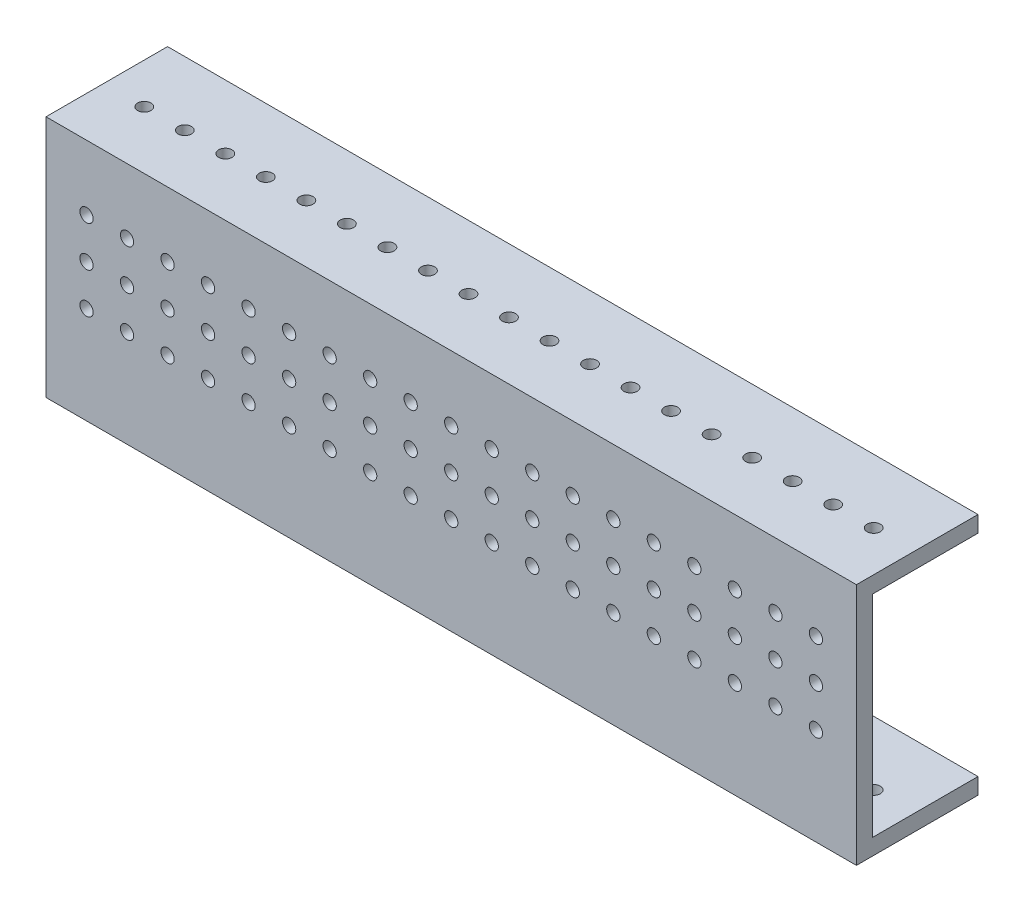
SolidWorks part; units mm, degrees
material "6061-T6 (SS)"
ref_plane "Front" through (0, 0, 0) normal (0, 0, 1) x (1, 0, 0)
ref_plane "Top" through (0, 0, 0) normal (0, 1, 0) x (1, 0, 0)
ref_plane "Right" through (0, 0, 0) normal (1, 0, 0) x (0, 0, -1)
sketch "Sketch1" plane through (0, 0, 0) normal (1, 0, 0) x (0, 0, -1)
  line L0 (-13.97, 33.02) -> (19.05, 33.02)
  line L1 (-19.05, 38.1) -> (19.05, 38.1)
  line L2 (-19.05, 38.1) -> (-19.05, -38.1)
  line L3 (-19.05, -38.1) -> (19.05, -38.1)
  line L4 (19.05, 38.1) -> (19.05, -38.1) construction
  line L5 (-19.05, 38.1) -> (19.05, -38.1) construction
  line L6 (-19.05, -38.1) -> (19.05, 38.1) construction
  line L7 (-13.97, 33.02) -> (-13.97, -33.02)
  line L8 (-13.97, -33.02) -> (19.05, -33.02)
  line L9 (19.05, 38.1) -> (19.05, 33.02)
  line L10 (19.05, -38.1) -> (19.05, -33.02)
  point P0 (0, 0)
  dimension "D1" = 38.1
  dimension "D2" = 76.2
  dimension "D3" = 5.08
extrude "Boss-Extrude1" add sketch "Sketch1" along normal mid plane 254
sketch "Sketch2" plane through (0, 38.1, 0) normal (0, 1, 0) x (1, 0, 0)
  line L0 (127, 19.05) -> (-127, 19.05) construction
  line L2 (-127, 19.05) -> (-127, -19.05) construction
  circle A0 centre (-114.3, -0.9451) radius 2.0828
  circle A1 centre (-101.6, -0.9451) radius 2.0828
  circle A2 centre (-88.9, -0.9451) radius 2.0828
  circle A3 centre (-76.2, -0.9451) radius 2.0828
  circle A4 centre (-63.5, -0.9451) radius 2.0828
  circle A5 centre (-50.8, -0.9451) radius 2.0828
  circle A6 centre (-38.1, -0.9451) radius 2.0828
  circle A7 centre (-25.4, -0.9451) radius 2.0828
  circle A8 centre (-12.7, -0.9451) radius 2.0828
  circle A9 centre (0, -0.9451) radius 2.0828
  circle A10 centre (12.7, -0.9451) radius 2.0828
  circle A11 centre (25.4, -0.9451) radius 2.0828
  circle A12 centre (38.1, -0.9451) radius 2.0828
  circle A13 centre (50.8, -0.9451) radius 2.0828
  circle A14 centre (63.5, -0.9451) radius 2.0828
  circle A15 centre (76.2, -0.9451) radius 2.0828
  circle A16 centre (88.9, -0.9451) radius 2.0828
  circle A17 centre (101.6, -0.9451) radius 2.0828
  circle A18 centre (114.3, -0.9451) radius 2.0828
  dimension "D1" = 4.1656
  dimension "D4" = 12.7
  dimension "D2" = 19.9951
  dimension "D3" = 19
  dimension "D5" = 12.7
extrude "Cut-Extrude1" cut sketch "Sketch2" against normal through all
sketch "Sketch3" plane through (0, 0, 19.05) normal (0, 0, 1) x (1, 0, 0)
  line L0 (-127, 38.1) -> (-127, -38.1) construction
  line L1 (127, 38.1) -> (-127, 38.1) construction
  circle A1 centre (-114.3, 17.78) radius 2.0828
  circle A2 centre (-101.6, 17.78) radius 2.0828
  circle A3 centre (-88.9, 17.78) radius 2.0828
  circle A4 centre (-76.2, 17.78) radius 2.0828
  circle A5 centre (-63.5, 17.78) radius 2.0828
  circle A6 centre (-50.8, 17.78) radius 2.0828
  circle A7 centre (-38.1, 17.78) radius 2.0828
  circle A8 centre (-25.4, 17.78) radius 2.0828
  circle A9 centre (-12.7, 17.78) radius 2.0828
  circle A10 centre (0, 17.78) radius 2.0828
  circle A11 centre (12.7, 17.78) radius 2.0828
  circle A12 centre (25.4, 17.78) radius 2.0828
  circle A13 centre (38.1, 17.78) radius 2.0828
  circle A14 centre (50.8, 17.78) radius 2.0828
  circle A15 centre (63.5, 17.78) radius 2.0828
  circle A16 centre (76.2, 17.78) radius 2.0828
  circle A17 centre (88.9, 17.78) radius 2.0828
  circle A18 centre (101.6, 17.78) radius 2.0828
  circle A19 centre (114.3, 17.78) radius 2.0828
  circle A20 centre (-101.6, 5.08) radius 2.0828
  circle A21 centre (-88.9, 5.08) radius 2.0828
  circle A22 centre (-76.2, 5.08) radius 2.0828
  circle A23 centre (-63.5, 5.08) radius 2.0828
  circle A24 centre (-50.8, 5.08) radius 2.0828
  circle A25 centre (-38.1, 5.08) radius 2.0828
  circle A26 centre (-25.4, 5.08) radius 2.0828
  circle A27 centre (-12.7, 5.08) radius 2.0828
  circle A28 centre (0, 5.08) radius 2.0828
  circle A29 centre (12.7, 5.08) radius 2.0828
  circle A30 centre (25.4, 5.08) radius 2.0828
  circle A31 centre (38.1, 5.08) radius 2.0828
  circle A32 centre (50.8, 5.08) radius 2.0828
  circle A33 centre (63.5, 5.08) radius 2.0828
  circle A34 centre (76.2, 5.08) radius 2.0828
  circle A35 centre (88.9, 5.08) radius 2.0828
  circle A36 centre (101.6, 5.08) radius 2.0828
  circle A37 centre (114.3, 5.08) radius 2.0828
  circle A38 centre (-101.6, -7.62) radius 2.0828
  circle A39 centre (-88.9, -7.62) radius 2.0828
  circle A40 centre (-76.2, -7.62) radius 2.0828
  circle A41 centre (-63.5, -7.62) radius 2.0828
  circle A42 centre (-50.8, -7.62) radius 2.0828
  circle A43 centre (-38.1, -7.62) radius 2.0828
  circle A44 centre (-25.4, -7.62) radius 2.0828
  circle A45 centre (-12.7, -7.62) radius 2.0828
  circle A46 centre (0, -7.62) radius 2.0828
  circle A47 centre (12.7, -7.62) radius 2.0828
  circle A48 centre (25.4, -7.62) radius 2.0828
  circle A49 centre (38.1, -7.62) radius 2.0828
  circle A50 centre (50.8, -7.62) radius 2.0828
  circle A51 centre (63.5, -7.62) radius 2.0828
  circle A52 centre (76.2, -7.62) radius 2.0828
  circle A53 centre (88.9, -7.62) radius 2.0828
  circle A54 centre (101.6, -7.62) radius 2.0828
  circle A55 centre (114.3, -7.62) radius 2.0828
  circle A56 centre (-114.3, 5.08) radius 2.0828
  circle A57 centre (-114.3, -7.62) radius 2.0828
  point P121 (0, 0)
  dimension "D1" = 4.1656
  dimension "D6" = 12.7
  dimension "D2" = 20.32
  dimension "D3" = 12.7
  dimension "D7" = 12.7
  dimension "D4" = 19
  dimension "D5" = 3
extrude "Cut-Extrude2" cut sketch "Sketch3" against normal up to next (5.08 mm away)
